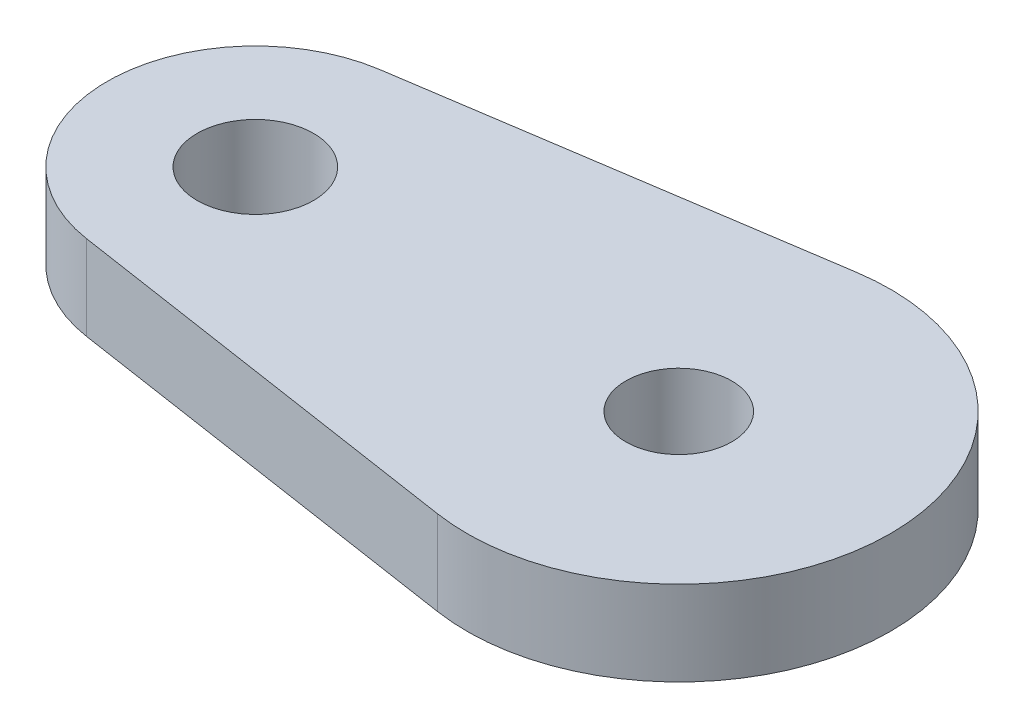
SolidWorks part; units mm, degrees
ref_plane "Front Plane" through (0, 0, 0) normal (0, 0, 1) x (1, 0, 0)
ref_plane "Top Plane" through (0, 0, 0) normal (0, 1, 0) x (1, 0, 0)
ref_plane "Right Plane" through (0, 0, 0) normal (1, 0, 0) x (0, 0, -1)
sketch "Sketch1" plane through (0, 0, 0) normal (0, 1, 0) x (1, 0, 0)
  line L0 (18.5, 9.8869) -> (-1.05, 6.9208)
  line L1 (-1.05, -6.9208) -> (18.5, -9.8869)
  circle A0 centre (0, 0) radius 2.75
  circle A1 centre (0, 0) radius 7
  circle A2 centre (20, 0) radius 2.5
  circle A3 centre (20, 0) radius 10
  point P11 (21.8306, 0)
  point P12 (18.7617, 9.3808)
  point P13 (0, 0)
  dimension "D1" = 5.5
  dimension "D2" = 14
  dimension "D4" = 20
  dimension "D5" = 5
  dimension "D3" = 20
extrude "Boss-Extrude1" add sketch "Sketch1" along normal blind 4 contours A1 A0 | A3 L0 A1 L1 | A3 A2
